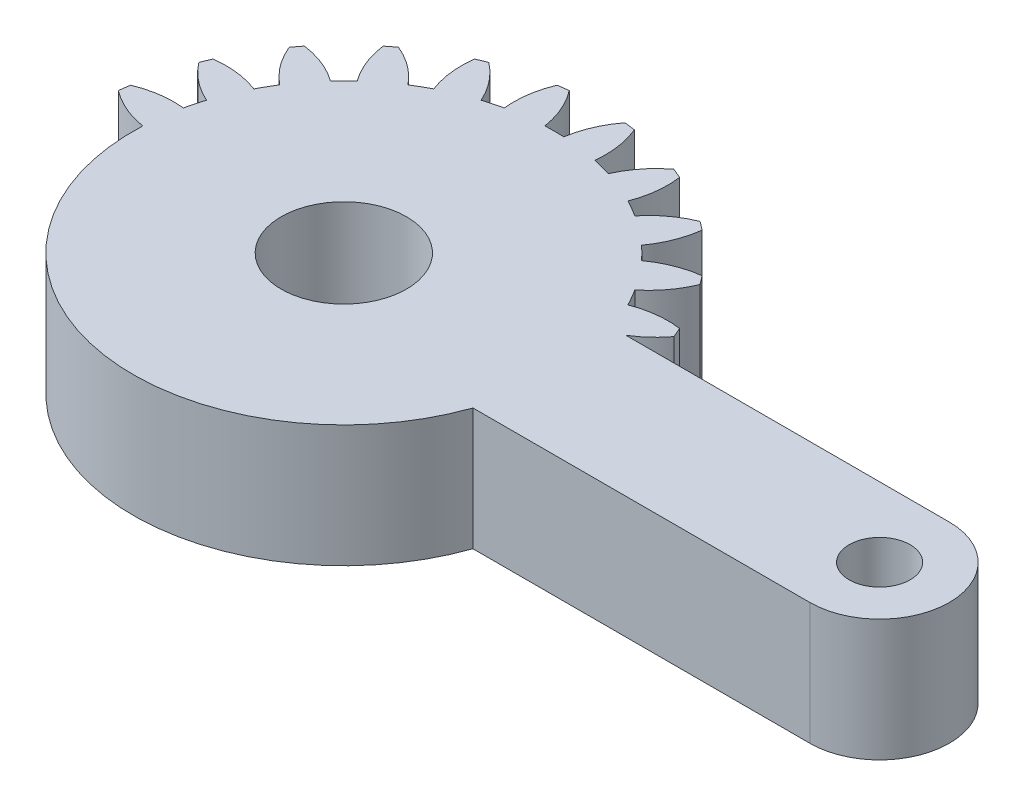
SolidWorks part; units mm, degrees
ref_plane "Front Plane" through (0, 0, 0) normal (0, 0, 1) x (1, 0, 0)
ref_plane "Top Plane" through (0, 0, 0) normal (0, 1, 0) x (1, 0, 0)
ref_plane "Right Plane" through (0, 0, 0) normal (1, 0, 0) x (0, 0, -1)
ref_plane "Plane1" through (0, 4, 0) normal (0, 1, 0) x (1, 0, 0)
sketch "Sketch1" plane through (0, 4, 0) normal (0, 1, 0) x (1, 0, 0)
  line L0 (1.3057, -4) -> (20.6437, -4)
  line L1 (20.6437, 4) -> (2.0816, 4)
  arc A0 (-24.5622, 2.2179) -> (-24.6437, 1.5991) centre (-10.1063, 0) ccw
  arc A1 (-24.6437, 1.5991) -> (-22.1869, 0.5427) centre (-21.3486, 5.8773) ccw
  arc A2 (-22.1869, 0.5427) -> (1.3057, -4) centre (-10.1063, 0) ccw
  arc A3 (20.6437, -4) -> (20.6437, 4) centre (20.6437, 0) ccw
  arc A4 (2.0816, 4) -> (3.5217, 5.3071) centre (-0.7683, 8.5867) ccw
  arc A5 (3.5217, 5.3071) -> (3.2829, 5.8838) centre (-10.1063, 0) ccw
  arc A6 (3.2829, 5.8838) -> (0.6271, 5.5703) centre (2.5684, 0.5313) ccw
  arc A7 (0.6271, 5.5703) -> (0.0844, 6.5103) centre (-10.1063, 0) ccw
  arc A8 (0.0844, 6.5103) -> (1.6838, 8.6535) centre (-3.3089, 10.711) ccw
  arc A9 (1.6838, 8.6535) -> (1.3038, 9.1487) centre (-10.1063, 0) ccw
  arc A10 (1.3038, 9.1487) -> (-1.1803, 8.1585) centre (1.999, 3.7936) ccw
  arc A11 (-1.1803, 8.1585) -> (-1.9479, 8.926) centre (-10.1063, 0) ccw
  arc A12 (-1.9479, 8.926) -> (-0.9576, 11.4102) centre (-6.3127, 12.1053) ccw
  arc A13 (-0.9576, 11.4102) -> (-1.4528, 11.7901) centre (-10.1063, 0) ccw
  arc A14 (-1.4528, 11.7901) -> (-3.596, 10.1907) centre (0.6046, 6.7975) ccw
  arc A15 (-3.596, 10.1907) -> (-4.5361, 10.7334) centre (-10.1063, 0) ccw
  arc A16 (-4.5361, 10.7334) -> (-4.2225, 13.3892) centre (-9.5751, 12.6747) ccw
  arc A17 (-4.2225, 13.3892) -> (-4.7992, 13.6281) centre (-10.1063, 0) ccw
  arc A18 (-4.7992, 13.6281) -> (-6.4554, 11.5285) centre (-1.5196, 9.3381) ccw
  arc A19 (-6.4554, 11.5285) -> (-7.5039, 11.8094) centre (-10.1063, 0) ccw
  arc A20 (-7.5039, 11.8094) -> (-7.8884, 14.4558) centre (-12.8736, 12.3803) ccw
  arc A21 (-7.8884, 14.4558) -> (-8.5072, 14.5373) centre (-10.1063, 0) ccw
  arc A22 (-8.5072, 14.5373) -> (-9.5636, 12.0806) centre (-4.2291, 11.2423) ccw
  arc A23 (-9.5636, 12.0806) -> (-10.6491, 12.0806) centre (-10.1063, 0) ccw
  arc A24 (-10.6491, 12.0806) -> (-11.7054, 14.5373) centre (-15.9836, 11.2423) ccw
  arc A25 (-11.7054, 14.5373) -> (-12.3243, 14.4558) centre (-10.1063, 0) ccw
  arc A26 (-12.3243, 14.4558) -> (-12.7088, 11.8094) centre (-7.3391, 12.3803) ccw
  arc A27 (-12.7088, 11.8094) -> (-13.7573, 11.5285) centre (-10.1063, 0) ccw
  arc A28 (-13.7573, 11.5285) -> (-15.4135, 13.6281) centre (-18.6931, 9.3381) ccw
  arc A29 (-15.4135, 13.6281) -> (-15.9901, 13.3892) centre (-10.1063, 0) ccw
  arc A30 (-15.9901, 13.3892) -> (-15.6766, 10.7334) centre (-10.6376, 12.6747) ccw
  arc A31 (-15.6766, 10.7334) -> (-16.6166, 10.1907) centre (-10.1063, 0) ccw
  arc A32 (-16.6166, 10.1907) -> (-18.7599, 11.7901) centre (-20.8173, 6.7975) ccw
  arc A33 (-18.7599, 11.7901) -> (-19.255, 11.4102) centre (-10.1063, 0) ccw
  arc A34 (-19.255, 11.4102) -> (-18.2648, 8.926) centre (-13.9, 12.1053) ccw
  arc A35 (-18.2648, 8.926) -> (-19.0324, 8.1585) centre (-10.1063, 0) ccw
  arc A36 (-19.0324, 8.1585) -> (-21.5165, 9.1487) centre (-22.2117, 3.7936) ccw
  arc A37 (-21.5165, 9.1487) -> (-21.8965, 8.6535) centre (-10.1063, 0) ccw
  arc A38 (-21.8965, 8.6535) -> (-20.2971, 6.5103) centre (-16.9038, 10.711) ccw
  arc A39 (-20.2971, 6.5103) -> (-20.8398, 5.5703) centre (-10.1063, 0) ccw
  arc A40 (-20.8398, 5.5703) -> (-23.4956, 5.8838) centre (-22.7811, 0.5313) ccw
  arc A41 (-23.4956, 5.8838) -> (-23.7344, 5.3071) centre (-10.1063, 0) ccw
  arc A42 (-23.7344, 5.3071) -> (-21.6348, 3.6509) centre (-19.4444, 8.5867) ccw
  arc A43 (-21.6348, 3.6509) -> (-21.9157, 2.6025) centre (-10.1063, 0) ccw
  arc A44 (-21.9157, 2.6025) -> (-24.5622, 2.2179) centre (-22.4867, -2.7673) ccw
  circle A45 centre (20.6437, 0) radius 1.75
  dimension "D1" = 3.5
  dimension "D4" = 5.4
  dimension "D5" = 14.625
  dimension "D6" = 4
  dimension "D7" = 5.4
  dimension "D8" = 12.0927
  dimension "D9" = 5.4
  dimension "D10" = 0.0844
  dimension "D11" = 5.4
  dimension "D12" = 0.6046
  dimension "D13" = 5.4
  dimension "D14" = 0.6271
  dimension "D15" = 5.4
  dimension "D16" = 1.3038
  dimension "D17" = 5.4
  dimension "D18" = 1.3057
  dimension "D19" = 5.4
  dimension "D20" = 1.6838
  dimension "D21" = 5.4
  dimension "D22" = 1.999
  dimension "D23" = 5.4
  dimension "D24" = 2.0816
  dimension "D25" = 5.4
  dimension "D26" = 2.5684
  dimension "D27" = 5.4
  dimension "D28" = 3.2829
  dimension "D29" = 5.4
  dimension "D30" = 3.5217
  dimension "D31" = 5.4
  dimension "D32" = 20.6437
  dimension "D33" = 5.4
  dimension "D34" = 0.9576
  dimension "D35" = 5.4
  dimension "D36" = 1.4528
  dimension "D37" = 5.4
  dimension "D38" = 1.5196
  dimension "D39" = 5.4
  dimension "D40" = 1.9479
  dimension "D41" = 5.4
  dimension "D42" = 4.2225
  dimension "D43" = 5.4
  dimension "D44" = 4.2291
  dimension "D45" = 5.4
  dimension "D46" = 4.5361
  dimension "D47" = 5.4
  dimension "D48" = 4.7992
  dimension "D49" = 7.3391
  dimension "D50" = 7.5039
  dimension "D51" = 7.8884
  dimension "D52" = 8.5072
  dimension "D53" = 10.6376
  dimension "D54" = 10.6491
  dimension "D55" = 11.7054
  dimension "D56" = 12.3243
  dimension "D57" = 13.7573
  dimension "D58" = 13.9
  dimension "D59" = 15.4135
  dimension "D60" = 15.6766
  dimension "D61" = 16.6166
  dimension "D62" = 16.9038
  dimension "D63" = 18.2648
  dimension "D64" = 18.7599
  dimension "D65" = 19.0324
  dimension "D66" = 19.4444
  dimension "D67" = 20.2971
  dimension "D68" = 20.8398
  dimension "D69" = 21.3486
  dimension "D70" = 21.5165
  dimension "D71" = 21.6348
  dimension "D72" = 21.9157
  dimension "D73" = 22.1869
  dimension "D74" = 22.4867
  dimension "D75" = 22.7811
  dimension "D76" = 0.5313
extrude "Boss-Extrude1" add sketch "Sketch1" against normal blind 7
sketch "草图1" plane through (0, -3, 0) normal (0, -1, 0) x (1, 0, 0)
  circle A0 centre (-10.1063, 0) radius 3.6
  point P6 (-10.1063, 0)
  dimension "D1" = 7.2
extrude "切除-拉伸1" cut sketch "草图1" against normal through all
ref_point "点1"
